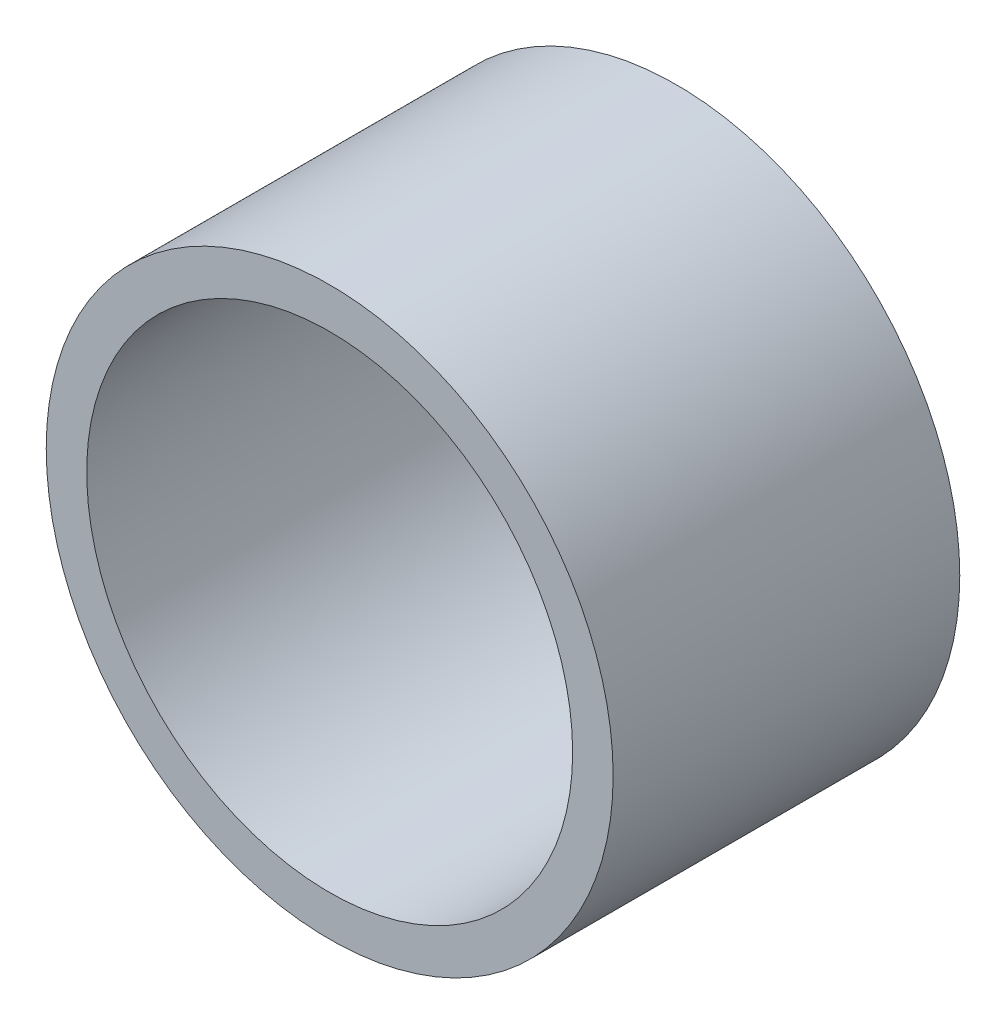
SolidWorks part; units mm, degrees
material "Rubber"
ref_plane "Front Plane" through (0, 0, 0) normal (0, 0, 1) x (1, 0, 0)
ref_plane "Top Plane" through (0, 0, 0) normal (0, 1, 0) x (1, 0, 0)
ref_plane "Right Plane" through (0, 0, 0) normal (1, 0, 0) x (0, 0, -1)
sketch "Sketch1" plane through (0, 0, 0) normal (0, 0, 1) x (1, 0, 0)
  circle A0 centre (0, 0) radius 9.525
  circle A1 centre (0, 0) radius 11.1125
  dimension "D1" = 19.05
  dimension "D2" = 1.5875
extrude "Boss-Extrude1" add sketch "Sketch1" along normal blind 13.589
